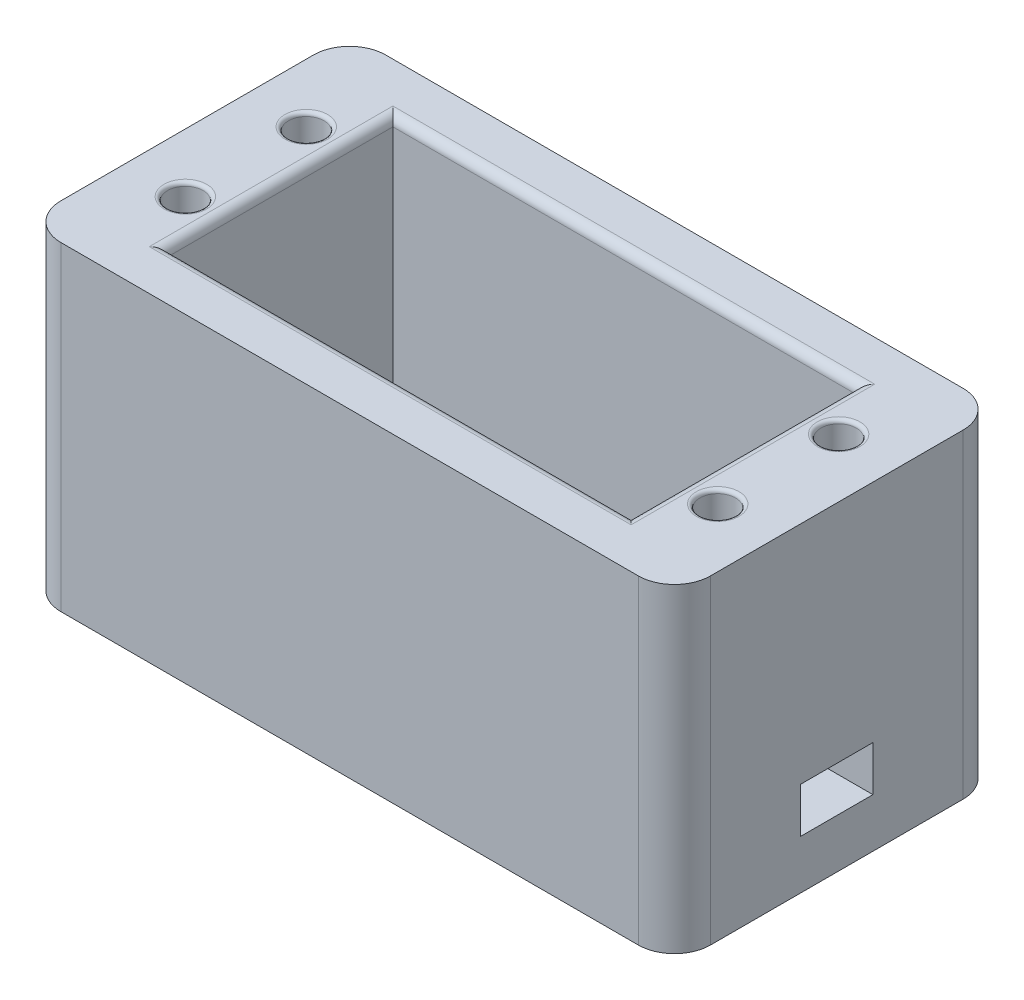
SolidWorks part; units mm, degrees
ref_plane "Front Plane" through (0, 0, 0) normal (0, 0, 1) x (1, 0, 0)
ref_plane "Top Plane" through (0, 0, 0) normal (0, 1, 0) x (1, 0, 0)
ref_plane "Right Plane" through (0, 0, 0) normal (1, 0, 0) x (0, 0, -1)
sketch "Sketch1" plane through (0, 0, 0) normal (0, 1, 0) x (1, 0, 0)
  line L1 (-45.72, 22.86) -> (45.72, 22.86)
  line L2 (-45.72, 22.86) -> (-45.72, -22.86)
  line L3 (-45.72, -22.86) -> (45.72, -22.86)
  line L4 (45.72, 22.86) -> (45.72, -22.86)
  line L5 (-45.72, 22.86) -> (45.72, -22.86) construction
  line L6 (-45.72, -22.86) -> (45.72, 22.86) construction
  point P0 (0, 0)
  point P6 (0, 0)
  dimension "D3" = 91.44
  dimension "D4" = 45.72
extrude "Boss-Extrude1" add sketch "Sketch1" along normal blind 45
sketch "Sketch2" plane through (0, 45, 0) normal (0, 1, 0) x (1, 0, 0)
  line L1 (-32.639, 15.875) -> (32.639, 15.875)
  line L2 (-32.639, 15.875) -> (-32.639, -15.875)
  line L3 (-32.639, -15.875) -> (32.639, -15.875)
  line L4 (32.639, 15.875) -> (32.639, -15.875)
  line L5 (-32.639, 15.875) -> (32.639, -15.875) construction
  line L6 (-32.639, -15.875) -> (32.639, 15.875) construction
  point P0 (0, 0)
  dimension "D1" = 65.278
  dimension "D2" = 31.75
extrude "Cut-Extrude1" cut sketch "Sketch2" against normal blind 40
sketch "Sketch3" plane through (0, 45, 0) normal (0, 1, 0) x (1, 0, 0)
  line L0 (0, 31.3041) -> (0, -31.3041) construction
  circle A0 centre (37.465, 8.509) radius 2.5
  circle A1 centre (37.465, -8.509) radius 2.5
  circle A2 centre (-37.465, -8.509) radius 2.5
  circle A3 centre (-37.465, 8.509) radius 2.5
  dimension "D1" = 5
  dimension "D2" = 17.018
  dimension "D3" = 8.509
  dimension "D4" = 37.465
extrude "Cut-Extrude2" cut sketch "Sketch3" against normal blind 25.4
fillet "Fillet1" radius 5.08 4 edges at (-45.72, 22.5, 22.86) (-45.72, 22.5, -22.86) (45.72, 22.5, 22.86) (45.72, 22.5, -22.86)
fillet "Fillet3" radius 1.27 4 edges at (-32.639, 45, 0) (0, 45, 15.875) (32.639, 45, 0) (0, 45, -15.875)
fillet "Fillet4" radius 0.508 4 edges at (-37.465, 45, 6.009) (-37.465, 45, -11.009) (37.465, 45, 11.009) (37.465, 45, -6.009)
sketch "Sketch4" plane through (32.639, 0, 0) normal (-1, 0, 0) x (0, 0, 1)
  line L0 (15.875, 5) -> (-15.875, 5) construction
  line L1 (5.08, 6.905) -> (-5.08, 6.905)
  line L2 (5.08, 6.905) -> (5.08, 13.255)
  line L3 (5.08, 13.255) -> (-5.08, 13.255)
  line L4 (-5.08, 6.905) -> (-5.08, 13.255)
  line L5 (5.08, 6.905) -> (-5.08, 13.255) construction
  line L6 (5.08, 13.255) -> (-5.08, 6.905) construction
  line L7 (-15.875, 5) -> (15.875, 5) construction
  line L8 (-15.875, 5) -> (-15.875, 43.73) construction
  line L9 (15.875, 5) -> (15.875, 43.73) construction
  point P0 (0, 10.08)
  point P7 (0, 5)
  dimension "D1" = 5.08
  dimension "D2" = 6.35
  dimension "D3" = 10.16
extrude "Cut-Extrude3" cut sketch "Sketch4" against normal through all
